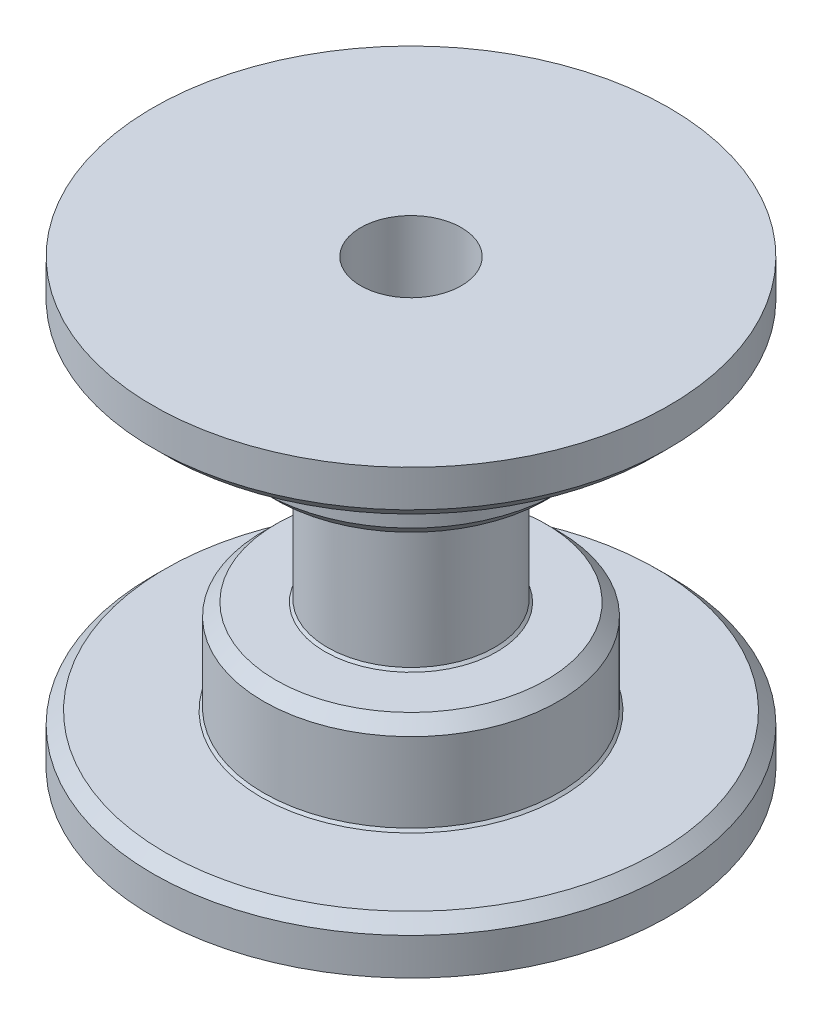
SolidWorks part; units mm, degrees
ref_plane "Alzado" through (0, 0, 0) normal (0, 0, 1) x (1, 0, 0)
ref_plane "Planta" through (0, 0, 0) normal (0, 1, 0) x (1, 0, 0)
ref_plane "Vista lateral" through (0, 0, 0) normal (1, 0, 0) x (0, 0, -1)
sketch "Sketch1" plane through (0, 0, 0) normal (1, 0, 0) x (0, 0, -1)
  line L0 (0, -56.1905) -> (0, 56.1905) construction
  line L1 (4.1, 18) -> (21, 18)
  line L2 (21, 18) -> (21, 14)
  line L3 (21, 14) -> (12, 14)
  line L4 (12, 14) -> (12, 6.35)
  line L5 (0, 0) -> (40.6757, 0) construction
  line L6 (4.1, 18) -> (4.1, -18)
  line L7 (12, 6.35) -> (6.8, 6.35)
  line L8 (6.8, 6.35) -> (6.8, -6.35)
  line L9 (12, -6.35) -> (6.8, -6.35)
  line L10 (12, -14) -> (12, -6.35)
  line L11 (21, -14) -> (12, -14)
  line L12 (21, -18) -> (21, -14)
  line L13 (4.1, -18) -> (21, -18)
  point P4 (0, 0)
  point P15 (6.8, 0)
  point P21 (4.1, 0)
  dimension "D1" = 42
  dimension "D2" = 7.9
  dimension "D3" = 8.2
  dimension "D4" = 6.8
  dimension "D5" = 12.7
  dimension "D6" = 28
  dimension "D7" = 4
revolve "Revolve1" add sketch "Sketch1" angle 360 about L0
sketch "Sketch2" [suppressed] plane through (0, 0, 0) normal (0, 0, 1) x (1, 0, 0)
  line L0 (18.5, 20) -> (-18.5, 20) construction
  line L1 (0, 20) -> (18.5, 20)
  line L2 (0, 20) -> (0, 14)
  line L3 (0, 14) -> (18.5, 14)
  line L4 (18.5, 20) -> (18.5, 14)
  line L5 (0, 20) -> (18.5, 14) construction
  line L6 (0, 14) -> (18.5, 20) construction
  line L7 (18.5, -14) -> (-18.5, -14) construction
  line L8 (0, -14) -> (18.5, -14)
  line L9 (0, -14) -> (0, -20)
  line L10 (0, -20) -> (18.5, -20)
  line L11 (18.5, -14) -> (18.5, -20)
  line L12 (0, -14) -> (18.5, -20) construction
  line L13 (0, -20) -> (18.5, -14) construction
  line L14 (-18.5, -20) -> (18.5, -20) construction
  point P4 (9.25, 17)
  point P12 (9.25, -17)
revolve "Cut-Revolve1" [suppressed] cut sketch "Sketch2" angle 360 about L2
chamfer "Chamfer1" distance 1 angle 45 4 edges at (0, -14, -21) (0, -6.35, -12) (0, 14, -21) (0, 6.35, -12)
chamfer "Chamfer2" distance 0.2 angle 45 4 edges at (0, 14, -12) (0, 6.35, -6.8) (0, -6.35, -6.8) (0, -14, -12)
